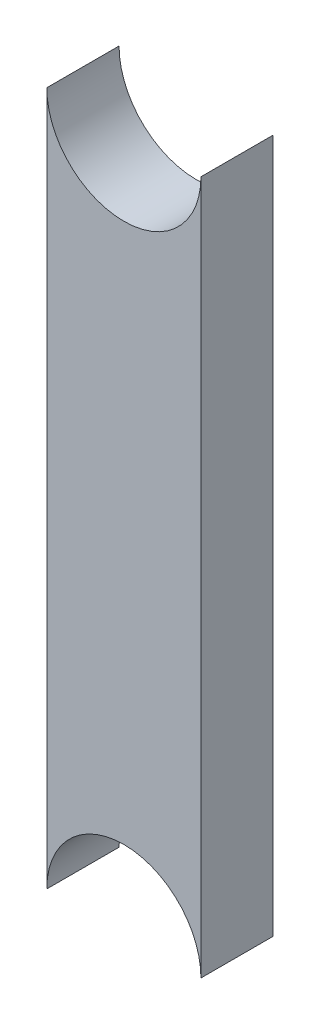
SolidWorks part; units mm, degrees
ref_plane "Front Plane" through (0, 0, 0) normal (0, 0, 1) x (1, 0, 0)
ref_plane "Top Plane" through (0, 0, 0) normal (0, 1, 0) x (1, 0, 0)
ref_plane "Right Plane" through (0, 0, 0) normal (1, 0, 0) x (0, 0, -1)
sketch "Sketch1" plane through (0, 0, 0) normal (0, 0, 1) x (1, 0, 0)
  line L1 (-3.2, 0) -> (-3.2, 28.8)
  line L2 (3.2, 28.8) -> (3.2, 0)
  line L3 (0, -1.65) -> (0, 1.65) construction
  arc A2 (3.2, 0) -> (-3.2, 0) centre (0, 0) ccw
  arc A3 (-3.2, 28.8) -> (3.2, 28.8) centre (0, 28.8) ccw
  dimension "D1" = 6.4
  dimension "D2" = 28.8
extrude "Boss-Extrude3" add sketch "Sketch1" along normal blind 3
equation "\"bScale\"= 8"
equation "\"lScale\"= 8"
equation "\"D1@Sketch1\"=.8*\"bScale\""
equation "\"D2@Sketch1\"=3.6*\"lScale\""
